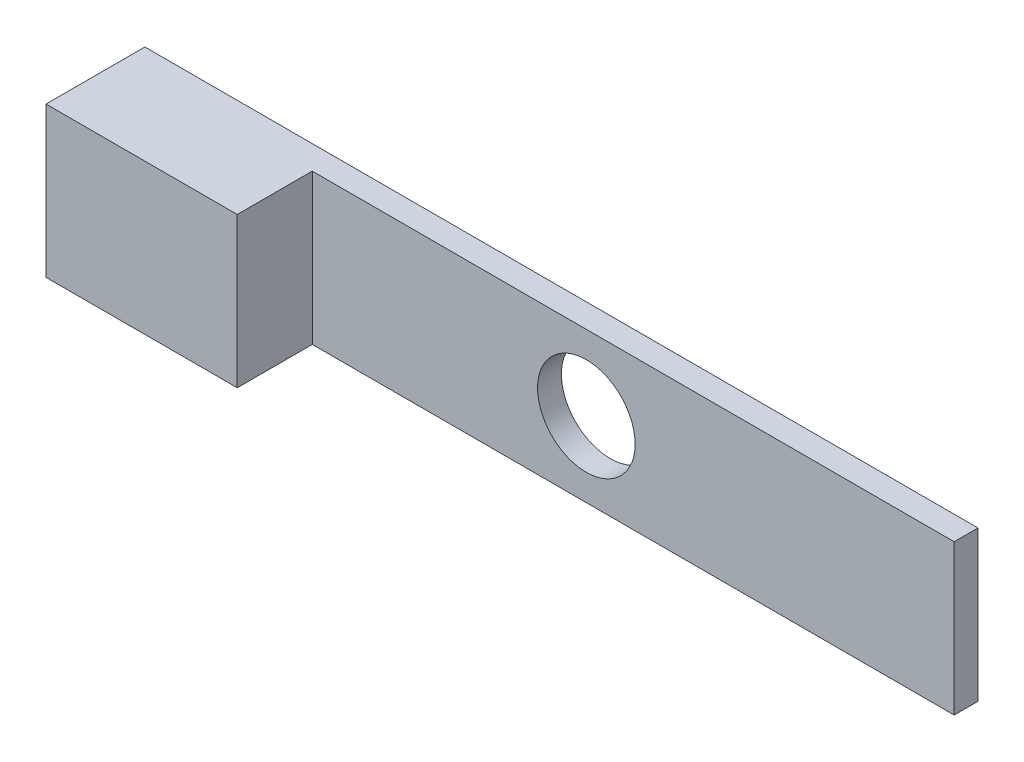
SolidWorks part; units mm, degrees
ref_plane "Front Plane" through (0, 0, 0) normal (0, 0, 1) x (1, 0, 0)
ref_plane "Top Plane" through (0, 0, 0) normal (0, 1, 0) x (1, 0, 0)
ref_plane "Right Plane" through (0, 0, 0) normal (1, 0, 0) x (0, 0, -1)
sketch "Sketch1" plane through (0, 0, 0) normal (0, 0, 1) x (1, 0, 0)
  line L0 (-112.5387, 0) -> (0, 0) construction
  line L2 (-112.5387, -10) -> (-1.5251, -10)
  line L4 (-112.5387, 10) -> (1.5251, 10)
  line L6 (-112.5387, -10) -> (-112.5387, 10)
  line L8 (-1.5251, -10) -> (-1.5251, 10)
  dimension "D6" = 112.5387
  dimension "D1" = 1.5251
  dimension "D3" = 10
  dimension "D2" = 1.5251
extrude "Boss-Extrude3" add sketch "Sketch1" along normal mid plane 3.175 contours L6 L0 L8 L4 | L0 L6 L2 L8
sketch "Sketch2" plane through (0, 0, 1.5875) normal (0, 0, 1) x (1, 0, 0)
  line L0 (-112.5387, 0) -> (-1.5251, 0) construction
  line L1 (-112.5387, -10) -> (-112.5387, 10) construction
  line L2 (-1.5251, -10) -> (-1.5251, 10) construction
  circle A0 centre (-50.5387, 0) radius 6.5
  dimension "D2" = 13
  dimension "D1" = 62
extrude "Cut-Extrude1" cut sketch "Sketch2" against normal through all both
sketch "Sketch3" plane through (0, 0, 1.5875) normal (0, 0, 1) x (1, 0, 0)
  line L0 (-112.5387, -10) -> (-1.5251, -10) construction
  line L1 (-112.5387, 10) -> (-87.0556, 10)
  line L2 (-112.5387, 10) -> (-112.5387, -10)
  line L3 (-112.5387, -10) -> (-87.0556, -10)
  line L4 (-87.0556, 10) -> (-87.0556, -10)
  line L5 (-112.5387, -10) -> (-112.5387, 10) construction
  dimension "D1" = 25.483
extrude "Boss-Extrude4" add sketch "Sketch3" along normal blind 10
